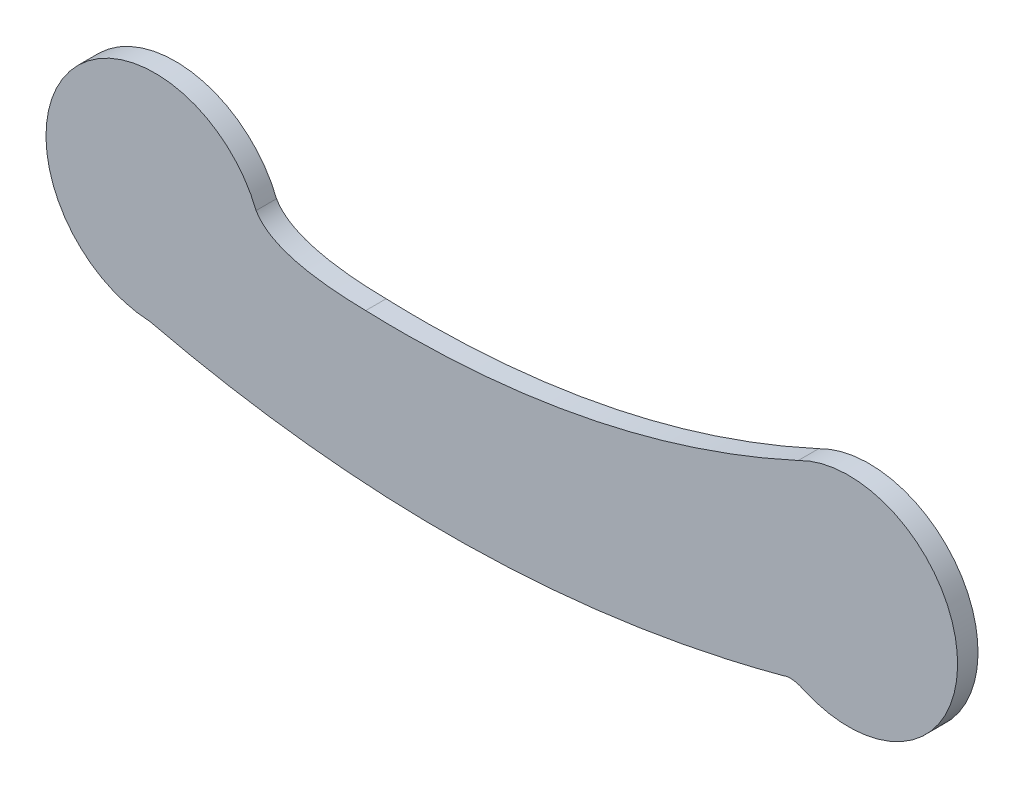
SolidWorks part; units mm, degrees
material "1060-H12"
ref_plane "Front Plane" through (0, 0, 0) normal (0, 0, 1) x (1, 0, 0)
ref_plane "Top Plane" through (0, 0, 0) normal (0, 1, 0) x (1, 0, 0)
ref_plane "Right Plane" through (0, 0, 0) normal (1, 0, 0) x (0, 0, -1)
sketch "Sketch1" plane through (0, 0, 0) normal (0, 0, 1) x (1, 0, 0)
  circle A0 centre (75.3616, -26.747) radius 5
  circle A1 centre (75.3616, -18.747) radius 1.1
  circle A2 centre (81.0185, -21.0901) radius 1.1
  circle A3 centre (83.3616, -26.747) radius 1.1
  circle A4 centre (-26.5181, -26.5149) radius 4
  circle A5 centre (81.0185, -32.4038) radius 1.1
  circle A6 centre (-26.5165, -18.5165) radius 1.1
  circle A7 centre (-20.8597, -20.8597) radius 1.1
  circle A8 centre (-18.5165, -26.5165) radius 1.1
  circle A9 centre (-20.8597, -32.1734) radius 1.1
  circle A10 centre (-26.5165, -34.5165) radius 1.1
  circle A11 centre (-32.1734, -32.1734) radius 1.1
  circle A12 centre (-34.5165, -26.5165) radius 1.1
  circle A13 centre (-32.1734, -20.8597) radius 1.1
  circle A14 centre (75.3616, -34.747) radius 1.1
  circle A15 centre (69.7048, -32.4038) radius 1.1
  circle A16 centre (67.3616, -26.747) radius 1.1
  circle A17 centre (69.7048, -21.0901) radius 1.1
  arc A22 (-11.6583, -20.5832) -> (-27.2644, -42.4975) centre (-26.5181, -26.5149) ccw
  arc A23 (68.9359, -41.3999) -> (67.9573, -12.5633) centre (75.3616, -26.747) ccw
  spline S0 degree 2 poles (-11.6583, -20.5832) (-9.0657, -25.06) (4.4406, -25.2547) knots 0 0 0 1 1 1
  spline S1 degree 2 poles (68.9359, -41.3999) (67.0568, -40.5293) (65.8717, -41.0057) knots 0 0 0 1 1 1
  spline S4 degree 3 poles (-27.2644, -42.4975) (-25.3345, -42.9558) (-21.4523, -43.8161) (-13.7054, -45.2869) (-4.0064, -46.6675) (7.6383, -47.5868) (19.2892, -47.7688) (30.9419, -47.2128) (42.5916, -45.92) (52.2982, -44.2285) (60.0522, -42.5101) (63.9403, -41.5254) (65.8717, -41.0057) knots 0.004189 0.004189 0.004189 0.004189 0.066428 0.128666 0.253142 0.377618 0.502095 0.626571 0.751047 0.875524 0.937762 1 1 1 1
  spline S7 degree 3 poles (67.9573, -12.5633) (65.4556, -13.7139) (60.3648, -15.8829) (52.6836, -18.6413) (44.8961, -20.9333) (37.0154, -22.753) (29.0339, -24.103) (20.9508, -24.9835) (14.1236, -25.3251) (8.6146, -25.3641) (5.8288, -25.3031) (4.4406, -25.2547) knots 0.003419 0.003419 0.003419 0.003419 0.119867 0.236316 0.352765 0.469214 0.585663 0.702111 0.81856 0.876785 0.935009 0.935009 0.935009 0.935009
  dimension "D1" = 8
  dimension "D2" = 8
  dimension "D3" = 8
  dimension "D4" = 10
extrude "Boss-Extrude1" add sketch "Sketch1" along normal blind 3 contours A13 | A6 | A7 | A23 S7 S0 A22 S4 S1 A0 A1 A2 A3 A4 A5 A6 A7 A8 A9 A10 A11 A12 A13 A14 A15 A16 A17 | A8 | A9 | A10 | A11 | A12 | A4 | A3 | A2 | A1 | A17 | A16 | A15 | A14 | A5 | A0
sketch "Sketch2" plane through (0, 0, 3) normal (0, 0, 1) x (1, 0, 0)
  line L0 (20.3616, -26.8313) -> (30.3616, -26.8313)
  line L1 (30.3616, -23.8313) -> (20.3616, -23.8313)
  line L2 (30.3616, -23.8313) -> (30.3616, -26.8313)
  line L4 (20.3616, -23.8313) -> (20.3616, -26.8313)
  line L5 (20.3616, -47.6255) -> (30.3616, -47.6255)
  line L6 (20.3616, -47.6255) -> (20.3616, -44.6255)
  line L8 (30.3616, -47.6255) -> (30.3616, -44.6255)
  line L9 (20.3616, -44.6255) -> (30.3616, -44.6255)
  circle A1 centre (25.3616, -31.8313) radius 1.35
  circle A2 centre (25.3616, -39.6255) radius 1.35
  circle A3 centre (75.3616, -26.747) radius 5 construction
  spline S0 degree 3 poles (67.9573, -12.5633) (65.4556, -13.7139) (60.3648, -15.8829) (52.6836, -18.6413) (44.8961, -20.9333) (37.0154, -22.753) (29.0339, -24.103) (20.9508, -24.9835) (14.1236, -25.3251) (8.6146, -25.3641) (5.8288, -25.3031) (4.4406, -25.2547) knots 0.003419 0.003419 0.003419 0.003419 0.119867 0.236316 0.352765 0.469214 0.585663 0.702111 0.81856 0.876785 0.935009 0.935009 0.935009 0.935009 construction
  spline S2 degree 3 poles (-27.2644, -42.4975) (-25.3345, -42.9558) (-21.4523, -43.8161) (-13.7054, -45.2869) (-4.0064, -46.6675) (7.6383, -47.5868) (19.2892, -47.7688) (30.9419, -47.2128) (42.5916, -45.92) (52.2982, -44.2285) (60.0522, -42.5101) (63.9403, -41.5254) (65.8717, -41.0057) knots 0.004189 0.004189 0.004189 0.004189 0.066428 0.128666 0.253142 0.377618 0.502095 0.626571 0.751047 0.875524 0.937762 1 1 1 1 construction
  dimension "D6" = 8
  dimension "D5" = 45
  dimension "D1" = 10
  dimension "D2" = 3
  dimension "D3" = 45
  dimension "D4" = 3
  dimension "D7" = 8
  dimension "D8" = 5
  dimension "D9" = 5
extrude "Cut-Extrude2" [suppressed] cut sketch "Sketch2" against normal blind 5
sketch "Sketch3" plane through (0, 0, 3) normal (0, 0, 1) x (1, 0, 0)
  line L1 (17.3616, -32.8476) -> (17.3616, -40.364)
  line L5 (33.3616, -31.2788) -> (33.3616, -38.9497)
  arc A0 (59.4146, -25.4453) -> (61.1867, -34.1679) centre (75.3616, -26.747) ccw
  arc A1 (-14.5511, -37.1353) -> (-11.0439, -30.583) centre (-26.5181, -26.5149) ccw
  arc A2 (-10.1763, -30.0811) -> (-11.0439, -30.583) centre (-10.3611, -30.7625) ccw
  arc A3 (-14.5511, -37.1353) -> (-14.3127, -38.0146) centre (-14.1438, -37.4968) ccw
  arc A4 (17.3616, -32.8476) -> (16.7005, -32.1844) centre (16.6983, -32.8476) ccw
  arc A5 (17.0899, -40.6679) -> (17.3616, -40.364) centre (17.0559, -40.364) ccw
  arc A6 (34.0436, -30.3347) -> (33.3616, -31.2788) centre (34.356, -31.2788) ccw
  arc A7 (33.3616, -38.9497) -> (34.1655, -39.772) centre (34.1841, -38.9497) ccw
  arc A8 (59.4146, -25.4453) -> (58.0677, -24.1217) centre (58.1891, -25.3452) ccw
  arc A9 (60.8864, -35.0698) -> (61.1867, -34.1679) centre (60.6018, -34.4741) ccw
  spline S0 degree 3 poles (4812.4556, -1334.984) (579.5946, 213.3231) (99.0418, -43.7558) (-3.4922, -31.7193) (-4.4979, -31.5677) (-6.4408, -31.1961) (-7.3781, -30.9762) (-9.1979, -30.4482) (-10.0807, -30.1402) (-11.802, -29.401) (-12.6415, -28.9695) (-14.2663, -27.9294) (-15.0528, -27.3189) (-46.7468, 4.253) (33.6784, 246.9473) (4914.6086, -774.9968) knots -11.8822 -11.8822 -11.8822 -11.8822 0.25 0.25 0.375 0.375 0.5 0.5 0.625 0.625 0.75 0.75 0.875 0.875 6.199801 6.199801 6.199801 6.199801 only from (4.3398, -32.254) to (-17.7158, -24.0912)
  spline S1 degree 3 poles (4.2676, -32.2529) (1.8526, -32.2162) (-0.3759, -32.0851) (-3.4922, -31.7193) (-4.4979, -31.5677) (-6.4408, -31.1961) (-7.3781, -30.9762) (-8.9304, -30.5258) (-9.5592, -30.3175) (-10.1763, -30.0811) knots 0.002465 0.002465 0.002465 0.002465 0.25 0.25 0.375 0.375 0.5 0.5 0.588246 0.588246 0.588246 0.588246
  spline S4 degree 3 poles (4918.5518, -753.9677) (-306.1128, 174.7884) (-154.1238, -9.3414) (-18.1745, -37.3131) (-16.3082, -37.6674) (-10.707, -38.642) (-6.9709, -39.1738) (4.235, -40.4136) (11.7047, -40.7666) (26.6497, -40.5268) (34.1237, -39.934) (45.3426, -38.334) (49.0842, -37.682) (54.6948, -36.5273) (56.5644, -36.113) (186.0918, -5.3541) (333.5349, 167.4963) (-4848.7356, -945.2678) knots -4.420614 -4.420614 -4.420614 -4.420614 0.0625 0.0625 0.125 0.125 0.25 0.25 0.5 0.5 0.75 0.75 0.875 0.875 0.9375 0.9375 5.196695 5.196695 5.196695 5.196695 only from (-25.6473, -35.6869) to (64.0532, -34.2461)
  spline S5 degree 3 poles (-14.3127, -38.0146) (-10.6214, -38.6542) (-6.9281, -39.1785) (3.5394, -40.3367) (10.3137, -40.6968) (17.0899, -40.6679) knots 0.126433 0.126433 0.126433 0.126433 0.25 0.25 0.476722 0.476722 0.476722 0.476722
  spline S7 degree 3 poles (-4701.9827, -1473.9753) (317.3361, 343.6662) (208.927, 34.9917) (60.2358, -23.3679) (57.5464, -24.3338) (49.4224, -26.9861) (43.9294, -28.4281) (32.8112, -30.6499) (27.1833, -31.4315) (18.6371, -32.1091) (15.7714, -32.2524) (11.4517, -32.3445) (10.007, -32.3547) (-106.2245, -31.4838) (-242.666, 100.8009) (4934.3168, -857.4567) knots -6.687967 -6.687967 -6.687967 -6.687967 0.125 0.125 0.25 0.25 0.5 0.5 0.75 0.75 0.875 0.875 0.9375 0.9375 5.875791 5.875791 5.875791 5.875791 only from (70.8822, -18.9229) to (4.1967, -32.2505)
  spline S8 degree 3 poles (58.0677, -24.1217) (56.9939, -24.5002) (55.9176, -24.8655) (49.4224, -26.9861) (43.9294, -28.4281) (36.9327, -29.8263) (35.4905, -30.0915) (34.0436, -30.3347) knots 0.200185 0.200185 0.200185 0.200185 0.25 0.25 0.5 0.5 0.564651 0.564651 0.564651 0.564651
  spline S10 degree 3 poles (4918.5518, -753.9677) (-306.1128, 174.7884) (-154.1238, -9.3414) (-18.1745, -37.3131) (-16.3082, -37.6674) (-10.707, -38.642) (-6.9709, -39.1738) (4.235, -40.4136) (11.7047, -40.7666) (26.6497, -40.5268) (34.1237, -39.934) (45.3426, -38.334) (49.0842, -37.682) (54.6948, -36.5273) (56.5644, -36.113) (186.0918, -5.3541) (333.5349, 167.4963) (-4848.7356, -945.2678) knots -4.420614 -4.420614 -4.420614 -4.420614 0.0625 0.0625 0.125 0.125 0.25 0.25 0.5 0.5 0.75 0.75 0.875 0.875 0.9375 0.9375 5.196695 5.196695 5.196695 5.196695 only from (-25.6473, -35.6869) to (64.0532, -34.2461)
  spline S11 degree 3 poles (34.1655, -39.772) (36.6442, -39.5225) (39.1233, -39.2209) (45.3426, -38.334) (49.0842, -37.682) (54.6948, -36.5273) (56.5644, -36.113) (59.2536, -35.4744) (60.0703, -35.2748) (60.8864, -35.0698) knots 0.667115 0.667115 0.667115 0.667115 0.75 0.75 0.875 0.875 0.9375 0.9375 0.964723 0.964723 0.964723 0.964723
  spline S12 degree 3 poles (-4701.9827, -1473.9753) (317.3361, 343.6662) (208.927, 34.9917) (60.2358, -23.3679) (57.5464, -24.3338) (49.4224, -26.9861) (43.9294, -28.4281) (32.8112, -30.6499) (27.1833, -31.4315) (18.6371, -32.1091) (15.7714, -32.2524) (11.4517, -32.3445) (10.007, -32.3547) (-106.2245, -31.4838) (-242.666, 100.8009) (4934.3168, -857.4567) knots -6.687967 -6.687967 -6.687967 -6.687967 0.125 0.125 0.25 0.25 0.5 0.5 0.75 0.75 0.875 0.875 0.9375 0.9375 5.875791 5.875791 5.875791 5.875791 only from (70.8822, -18.9229) to (4.1967, -32.2505)
  spline S13 degree 3 poles (16.7005, -32.1844) (15.4338, -32.2435) (14.1641, -32.2866) (11.4517, -32.3445) (10.007, -32.3547) (7.1253, -32.3331) (5.693, -32.302) (4.2676, -32.2529) knots 0.819768 0.819768 0.819768 0.819768 0.875 0.875 0.9375 0.9375 0.998982 0.998982 0.998982 0.998982
  dimension "D1" = 7
  dimension "D2" = 7
  dimension "D3" = 7
  dimension "D4" = 7
  dimension "D5" = 7
extrude "Cut-Extrude3" [suppressed] cut sketch "Sketch3" against normal blind 3
sketch "Sketch4" plane through (0, 0, 3) normal (0, 0, 1) x (1, 0, 0)
  point P0 (-26.5181, -26.5149)
sketch "Sketch5" plane through (0, 0, 3) normal (0, 0, 1) x (1, 0, 0)
  line L0 (-26.5181, -26.5149) -> (75.3616, -26.747) construction
  point P4 (24.4218, -26.631)
